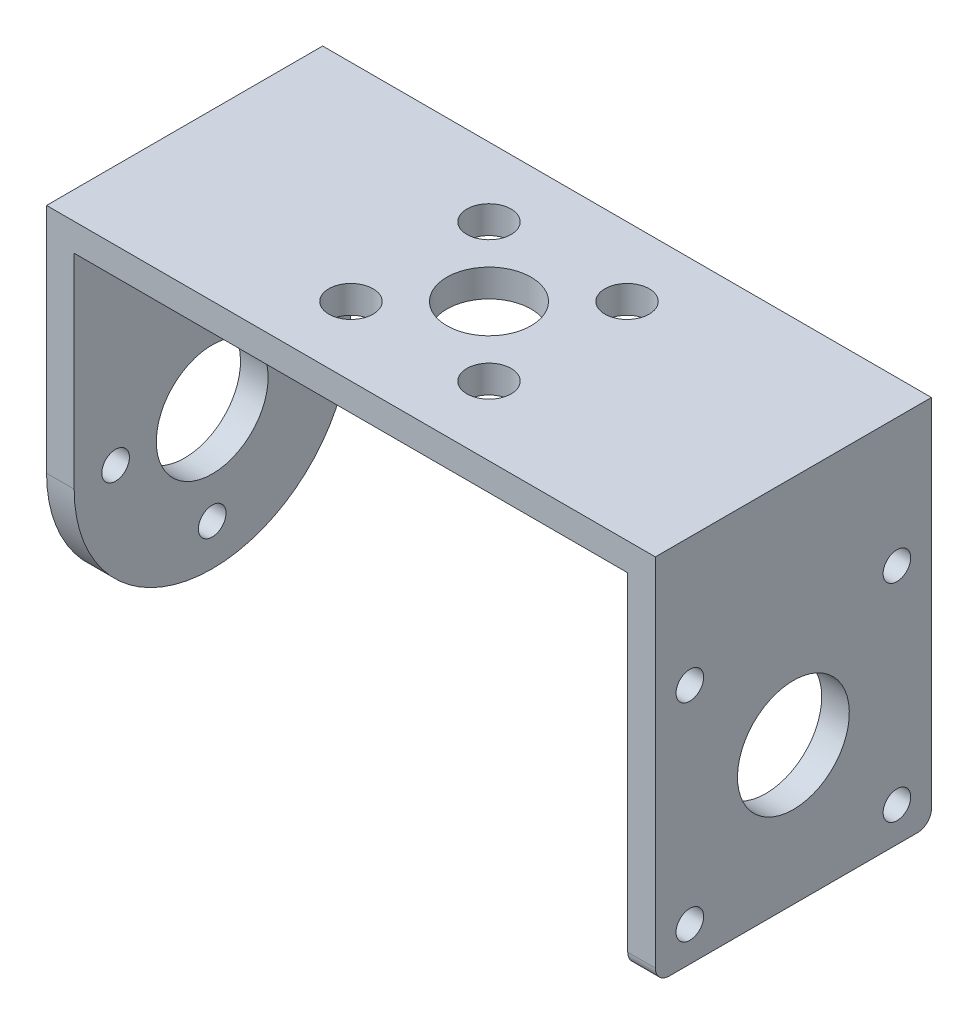
SolidWorks part; units mm, degrees
ref_plane "Plan de face" through (0, 0, 0) normal (0, 0, 1) x (1, 0, 0)
ref_plane "Plan de dessus" through (0, 0, 0) normal (0, 1, 0) x (1, 0, 0)
ref_plane "Plan de droite" through (0, 0, 0) normal (1, 0, 0) x (0, 0, -1)
sketch "Esquisse1" plane through (0, 0, 0) normal (0, 0, 1) x (1, 0, 0)
  line L0 (0, 0) -> (0, 26.8) construction
  line L1 (-22.05, 26.8) -> (22.05, 26.8)
  line L2 (22.05, 26.8) -> (22.05, 0)
  line L3 (22.05, 0) -> (20.05, 0)
  line L4 (20.05, 0) -> (20.05, 24.8)
  line L5 (20.05, 24.8) -> (-20.05, 24.8)
  line L6 (-22.05, 0) -> (-20.05, 0)
  line L7 (-20.05, 0) -> (-20.05, 24.8)
  line L8 (-22.05, 26.8) -> (-22.05, 0)
  point P11 (0, 24.8)
  dimension "D1" = 2
  dimension "D2" = 2
  dimension "D3" = 44.1
  dimension "D4" = 26.8
extrude "Boss.-Extru.1" add sketch "Esquisse1" along normal mid plane 20
sketch "Esquisse6" plane through (0, 26.8, 0) normal (0, 1, 0) x (1, 0, 0)
  line L1 (-5, 5) -> (5, 5) construction
  line L2 (-5, 5) -> (-5, -5) construction
  line L3 (-5, -5) -> (5, -5) construction
  line L4 (5, 5) -> (5, -5) construction
  circle A0 centre (0, 0) radius 3.05
  circle A1 centre (0, 0) radius 7.0711 construction
  circle A2 centre (-5, 5) radius 1.6
  circle A3 centre (5, 5) radius 1.6
  circle A4 centre (5, -5) radius 1.6
  circle A5 centre (-5, -5) radius 1.6
  dimension "D1" = 10
  dimension "D2" = 3.2
  dimension "D3" = 6.1
extrude "Enlèv. mat.-Extru.4" cut sketch "Esquisse6" against normal through all
sketch "Esquisse3" plane through (-22.05, 0, 0) normal (-1, 0, 0) x (0, 0, 1)
  line L0 (0, 0) -> (0, 10) construction
  line L1 (-10, 26.8) -> (-10, 0) construction
  line L2 (-10, 10) -> (-10, 0)
  line L3 (-10, 0) -> (10, 0)
  line L4 (10, 10) -> (10, 0)
  arc A0 (-10, 10) -> (10, 10) centre (0, 10) ccw
  line M5 (-10, 26.8) -> (-10, 0)
  line M6 (-10, 0) -> (10, 0)
  line M7 (10, 0) -> (10, 26.8)
extrude "Enlèv. mat.-Extru.1" cut sketch "Esquisse3" against normal up to next and the other way through all contours A0 M5 M6 | A0 L3 M7
sketch "Esquisse4" plane through (-22.05, 0, 0) normal (-1, 0, 0) x (0, 0, 1)
  circle A0 centre (0, 10) radius 4.05
  dimension "D1" = 8.1
extrude "Enlèv. mat.-Extru.2" cut sketch "Esquisse4" against normal through all
sketch "Esquisse5" plane through (-22.05, 0, 0) normal (-1, 0, 0) x (0, 0, 1)
  line L0 (-7, 10) -> (0, 10) construction
  line L1 (-7, 10) -> (0, 17) construction
  line L2 (-7, 10) -> (0, 3) construction
  line L3 (0, 3) -> (7, 10) construction
  line L4 (0, 17) -> (7, 10) construction
  circle A0 centre (0, 10) radius 7 construction
  circle A1 centre (-7, 10) radius 1
  circle A2 centre (0, 17) radius 1
  circle A3 centre (7, 10) radius 1
  circle A4 centre (0, 3) radius 1
  dimension "D1" = 14
  dimension "D2" = 2
extrude "Enlèv. mat.-Extru.3" cut sketch "Esquisse5" against normal up to next
sketch "Esquisse7" plane through (22.05, 0, 0) normal (1, 0, 0) x (0, 0, -1)
  line L1 (-7.5, 17.5) -> (7.5, 17.5) construction
  line L2 (-7.5, 17.5) -> (-7.5, 2.5) construction
  line L3 (-7.5, 2.5) -> (7.5, 2.5) construction
  line L4 (7.5, 17.5) -> (7.5, 2.5) construction
  circle A0 centre (0, 10) radius 10.6066 construction
  circle A1 centre (-7.5, 2.5) radius 1
  circle A2 centre (7.5, 2.5) radius 1
  circle A3 centre (7.5, 17.5) radius 1
  circle A4 centre (-7.5, 17.5) radius 1
  dimension "D1" = 2
  dimension "D2" = 15
extrude "Enlèv. mat.-Extru.5" cut sketch "Esquisse7" against normal up to next
fillet "Congé1" radius 1 2 edges at (21.05, 0, -10) (21.05, 0, 10)
equation "\"D2@Esquisse1\"=\"D1@Esquisse1\""
